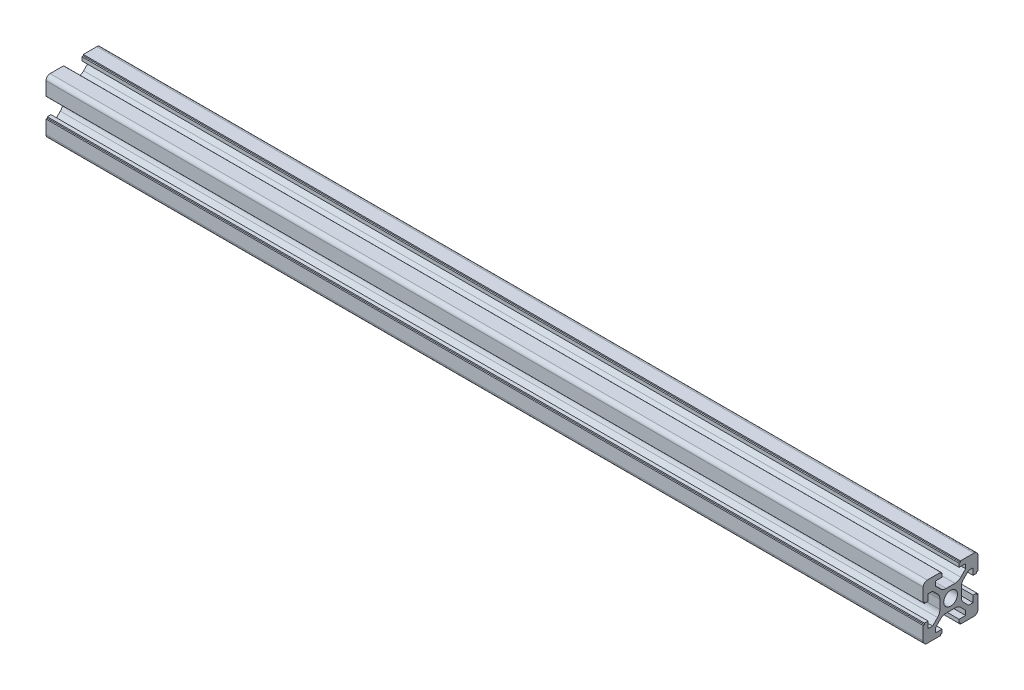
SolidWorks part; units mm, degrees
ref_plane "前视基准面" through (0, 0, 0) normal (0, 0, 1) x (1, 0, 0)
ref_plane "上视基准面" through (0, 0, 0) normal (0, 1, 0) x (1, 0, 0)
ref_plane "右视基准面" through (0, 0, 0) normal (1, 0, 0) x (0, 0, -1)
sketch "草图1" plane through (0, 0, 0) normal (1, 0, 0) x (0, 0, -1)
  line L0 (0, 0) -> (-10, 0) construction
  line L1 (0, 0) -> (0, 10) construction
  line L2 (0, 0) -> (-10, 10) construction
  line L3 (-10, 10) -> (-10, 3.6)
  line L4 (-10, 3.6) -> (-9.531, 3.6)
  line L5 (-9.531, 3.6) -> (-9.531, 3.1)
  line L6 (-9.531, 3.1) -> (-8.2, 3.1)
  line L7 (-8.2, 3.1) -> (-8.2, 5.5)
  line L8 (-8.2, 5.5) -> (-6.5607, 5.5)
  line L9 (-6.5607, 5.5) -> (-3.9, 2.8393)
  line L10 (-3.9, 2.8393) -> (-3.9, 0)
  line L11 (-3.6, 9.531) -> (-3.1, 9.531)
  line L12 (-2.8393, 3.9) -> (0, 3.9)
  line L13 (-5.5, 6.5607) -> (-2.8393, 3.9)
  line L14 (-5.5, 8.2) -> (-5.5, 6.5607)
  line L15 (-3.1, 8.2) -> (-5.5, 8.2)
  line L16 (-3.1, 9.531) -> (-3.1, 8.2)
  line L17 (-3.6, 10) -> (-3.6, 9.531)
  line L18 (-10, 10) -> (-3.6, 10)
  line L19 (0, 0) -> (0, 10) construction
  line L20 (0, 0) -> (10, 0) construction
  line L21 (0, 0) -> (10, 10) construction
  line L22 (10, 10) -> (3.6, 10)
  line L23 (3.6, 10) -> (3.6, 9.531)
  line L24 (3.6, 9.531) -> (3.1, 9.531)
  line L25 (3.1, 9.531) -> (3.1, 8.2)
  line L26 (3.1, 8.2) -> (5.5, 8.2)
  line L27 (5.5, 8.2) -> (5.5, 6.5607)
  line L28 (5.5, 6.5607) -> (2.8393, 3.9)
  line L29 (2.8393, 3.9) -> (0, 3.9)
  line L30 (9.531, 3.6) -> (9.531, 3.1)
  line L31 (3.9, 2.8393) -> (3.9, 0)
  line L32 (6.5607, 5.5) -> (3.9, 2.8393)
  line L33 (8.2, 5.5) -> (6.5607, 5.5)
  line L34 (8.2, 3.1) -> (8.2, 5.5)
  line L35 (9.531, 3.1) -> (8.2, 3.1)
  line L36 (10, 3.6) -> (9.531, 3.6)
  line L37 (10, 10) -> (10, 3.6)
  line L38 (0, 0) -> (10, 0) construction
  line L39 (0, 0) -> (0, -10) construction
  line L40 (0, 0) -> (10, -10) construction
  line L41 (10, -10) -> (10, -3.6)
  line L42 (10, -3.6) -> (9.531, -3.6)
  line L43 (9.531, -3.6) -> (9.531, -3.1)
  line L44 (9.531, -3.1) -> (8.2, -3.1)
  line L45 (8.2, -3.1) -> (8.2, -5.5)
  line L46 (8.2, -5.5) -> (6.5607, -5.5)
  line L47 (6.5607, -5.5) -> (3.9, -2.8393)
  line L48 (3.9, -2.8393) -> (3.9, 0)
  line L49 (3.6, -9.531) -> (3.1, -9.531)
  line L50 (2.8393, -3.9) -> (0, -3.9)
  line L51 (5.5, -6.5607) -> (2.8393, -3.9)
  line L52 (5.5, -8.2) -> (5.5, -6.5607)
  line L53 (3.1, -8.2) -> (5.5, -8.2)
  line L54 (3.1, -9.531) -> (3.1, -8.2)
  line L55 (3.6, -10) -> (3.6, -9.531)
  line L56 (10, -10) -> (3.6, -10)
  line L57 (0, 0) -> (0, -10) construction
  line L58 (0, 0) -> (-10, 0) construction
  line L59 (0, 0) -> (-10, -10) construction
  line L60 (-10, -10) -> (-3.6, -10)
  line L61 (-3.6, -10) -> (-3.6, -9.531)
  line L62 (-3.6, -9.531) -> (-3.1, -9.531)
  line L63 (-3.1, -9.531) -> (-3.1, -8.2)
  line L64 (-3.1, -8.2) -> (-5.5, -8.2)
  line L65 (-5.5, -8.2) -> (-5.5, -6.5607)
  line L66 (-5.5, -6.5607) -> (-2.8393, -3.9)
  line L67 (-2.8393, -3.9) -> (0, -3.9)
  line L68 (-9.531, -3.6) -> (-9.531, -3.1)
  line L69 (-3.9, -2.8393) -> (-3.9, 0)
  line L70 (-6.5607, -5.5) -> (-3.9, -2.8393)
  line L71 (-8.2, -5.5) -> (-6.5607, -5.5)
  line L72 (-8.2, -3.1) -> (-8.2, -5.5)
  line L73 (-9.531, -3.1) -> (-8.2, -3.1)
  line L74 (-10, -3.6) -> (-9.531, -3.6)
  line L75 (-10, -10) -> (-10, -3.6)
  arc A0 (0, 2.5) -> (-2.5, 0) centre (0, 0) ccw
  arc A1 (2.5, 0) -> (0, 2.5) centre (0, 0) ccw
  arc A2 (0, -2.5) -> (2.5, 0) centre (0, 0) ccw
  arc A3 (-2.5, 0) -> (0, -2.5) centre (0, 0) ccw
  point P89 (0, 0)
  dimension "D3" = 5
  dimension "D1" = 10
  dimension "D2" = 10
  dimension "D4" = 10
  dimension "D5" = 1.8
  dimension "D6" = 5.5
  dimension "D7" = 3.1
  dimension "D8" = 3.6
  dimension "D9" = 6.1
  dimension "D10" = 0.75
  dimension "D11" = 4
extrude "凸台-拉伸1" add sketch "草图1" along normal blind 320
fillet "圆角1" radius 1.5 4 edges at (160, -10, -10) (160, -10, 10) (160, 10, -10) (160, 10, 10)
fillet "圆角2" radius 3 8 edges at (160, -3.9, 2.8393) (160, -3.9, -2.8393) (160, -2.8393, -3.9) (160, 2.8393, -3.9) (160, 2.8393, 3.9) (160, -2.8393, 3.9) (160, 3.9, 2.8393) (160, 3.9, -2.8393)
